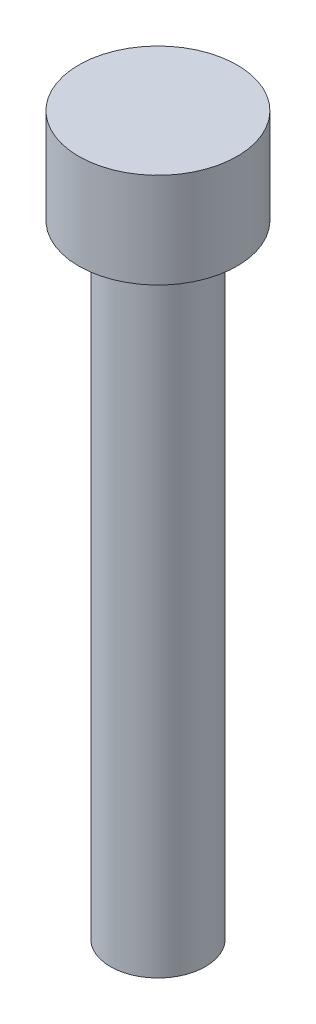
SolidWorks part; units mm, degrees
ref_plane "Front Plane" through (0, 0, 0) normal (0, 0, 1) x (1, 0, 0)
ref_plane "Top Plane" through (0, 0, 0) normal (0, 1, 0) x (1, 0, 0)
ref_plane "Right Plane" through (0, 0, 0) normal (1, 0, 0) x (0, 0, -1)
sketch "Sketch1" plane through (0, 0, 0) normal (0, 1, 0) x (1, 0, 0)
  circle A0 centre (0, 0) radius 3
  dimension "D1" = 6
extrude "Boss-Extrude1" add sketch "Sketch1" along normal blind 39.3
sketch "Sketch2" plane through (0, 39.3, 0) normal (0, 1, 0) x (1, 0, 0)
  circle A0 centre (0, 0) radius 5
  dimension "D1" = 10
extrude "Boss-Extrude2" add sketch "Sketch2" along normal blind 6
